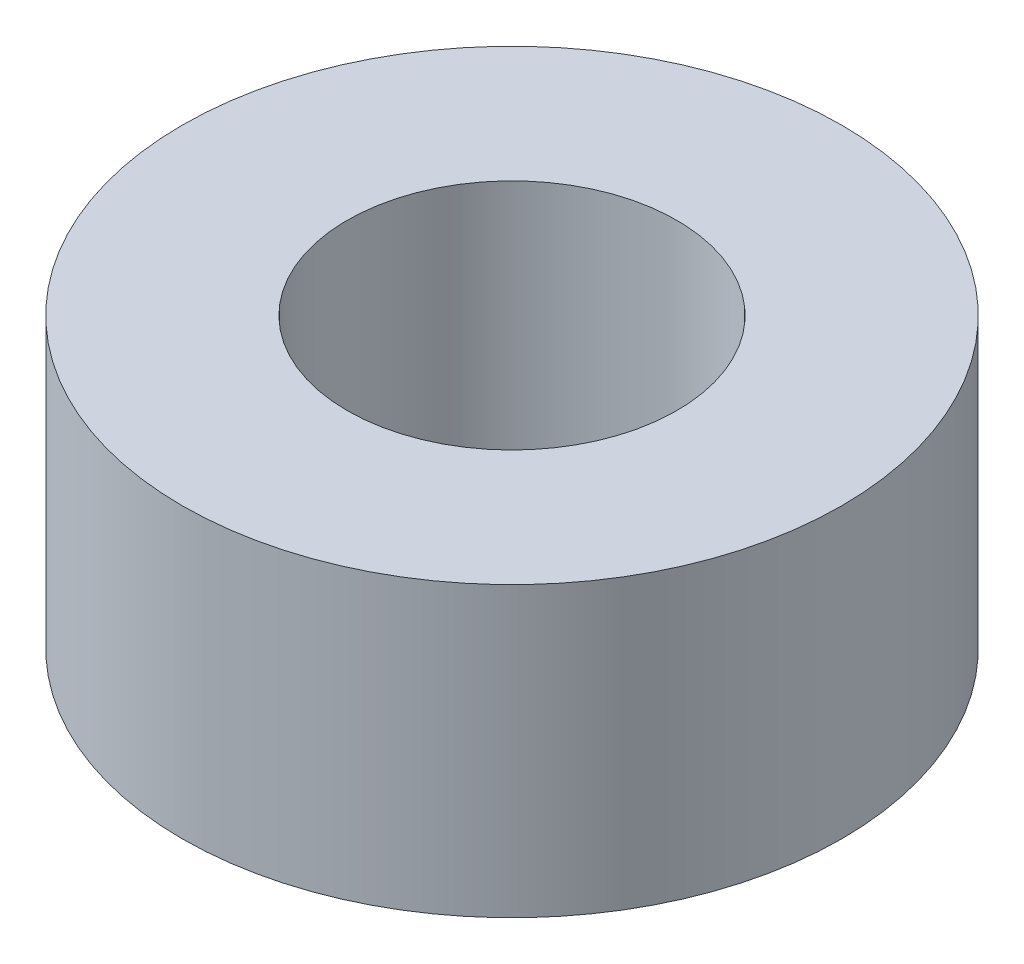
SolidWorks part; units mm, degrees
material "AISI 304"
ref_plane "前视基准面" through (0, 0, 0) normal (0, 0, 1) x (1, 0, 0)
ref_plane "上视基准面" through (0, 0, 0) normal (0, 1, 0) x (1, 0, 0)
ref_plane "右视基准面" through (0, 0, 0) normal (1, 0, 0) x (0, 0, -1)
other "Configuration Table"
sketch "草图1" plane through (0, 0, 0) normal (0, 1, 0) x (1, 0, 0)
  circle A0 centre (0, 0) radius 2
  circle A1 centre (0, 0) radius 4
  dimension "D1" = 4
  dimension "D2" = 8
extrude "凸台-拉伸1" add sketch "草图1" along normal blind 3.5
